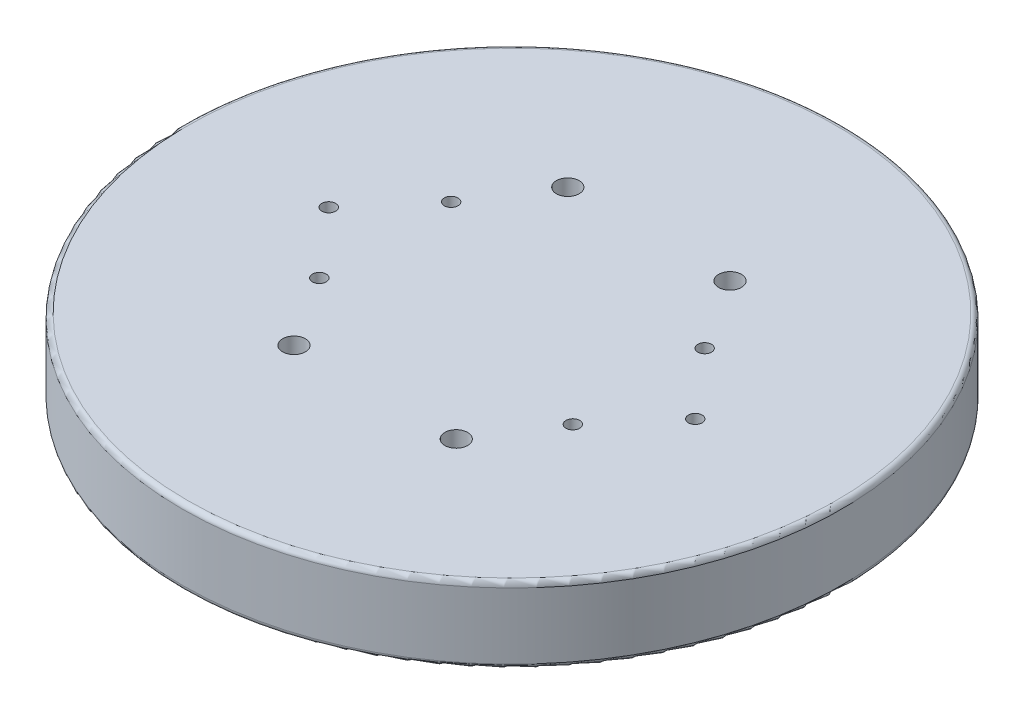
SolidWorks part; units mm, degrees
material "Delrin 2700 NC010, Low Viscosity Acetal Copolymer (SS)"
ref_plane "Front Plane" through (0, 0, 0) normal (0, 0, 1) x (1, 0, 0)
ref_plane "Top Plane" through (0, 0, 0) normal (0, 1, 0) x (1, 0, 0)
ref_plane "Right Plane" through (0, 0, 0) normal (1, 0, 0) x (0, 0, -1)
sketch "Sketch1" plane through (0, 0, 0) normal (0, 1, 0) x (1, 0, 0)
  circle A0 centre (0, 0) radius 65
  dimension "D1" = 130
extrude "Boss-Extrude1" add sketch "Sketch1" along normal blind 15
fillet "Fillet1" radius 1 2 edges at (0, 0, 65) (0, 15, 65)
hole_wizard "#6-32 Tapped Hole1" positions "Sketch2" profile "Sketch3" tap size "#6-32" standard "ANSI Inch" end condition through all
sketch "Sketch2" plane through (0, 0, 0) normal (0, 1, 0) x (1, 0, 0)
  point P0 (-36.145, 0)
  point P2 (36.145, 0)
  point P4 (-25, 13)
  point P6 (-25, -13)
  point P8 (25, -13)
  point P10 (25, 13)
  dimension "D1" = 36.145
  dimension "D2" = 36.145
  dimension "D3" = 25
  dimension "D4" = 25
  dimension "D5" = 13
  dimension "D6" = 13
sketch "Sketch3" plane through (-36.145, 0, 0) normal (1, 0, 0) x (0, 0, -1)
  line L0 (0, 0) -> (0, 15)
  line L1 (0, 15) -> (1.3525, 15)
  line L2 (1.3525, 15) -> (1.3525, 0)
  line L5 (1.3525, 0) -> (0, 0)
  line L11 (0, -6.35) -> (0, 107.95) construction
  dimension "Thru Tap Drill Dia." = 2.7051
  dimension "Thru Tap Drill Depth" = 15
cosmetic thread "Hole Thread1" parameters "D2"=3.5052
cosmetic thread "Hole Thread2" parameters "D2"=3.5052
cosmetic thread "Hole Thread3" parameters "D2"=3.5052
cosmetic thread "Hole Thread4" parameters "D2"=3.5052
cosmetic thread "Hole Thread5" parameters "D2"=3.5052
cosmetic thread "Hole Thread6" parameters "D2"=3.5052
hole_wizard "#4-40 Tapped Hole1" [suppressed] positions "Sketch5" profile "Sketch6" tap size "#4-40" standard "ANSI Inch"
sketch "Sketch5" plane through (0, 0, 0) normal (0, -1, 0) x (-1, 0, 0)
  circle A0 centre (-36.145, 0) radius 1.3526 construction
  point P0 (-48.145, 27.124)
  point P2 (-48.145, -27.124)
  dimension "D1" = 12
  dimension "D2" = 27.124
  dimension "D3" = 27.124
sketch "Sketch6" plane through (48.145, 0, -27.124) normal (1, 0, 0) x (0, 0, -1)
  line L0 (0, 0) -> (0, 25.4)
  line L1 (0, 25.4) -> (1.1303, 25.4)
  line L2 (1.1303, 25.4) -> (1.1303, 0)
  line L5 (1.1303, 0) -> (0, 0)
  line L11 (0, -6.35) -> (0, 107.95) construction
  dimension "Thru Tap Drill Dia." = 2.2606
  dimension "Thru Tap Drill Depth" = 25.4
cosmetic thread "Hole Thread7" [suppressed] parameters "D2"=2.8448
cosmetic thread "Hole Thread8" [suppressed] parameters "D2"=2.8448
hole_wizard "#8 Clearance Hole1" positions "Sketch7" profile "Sketch8" hole size "#8" standard "ANSI Inch" end condition through all
sketch "Sketch7" plane through (0, 0, 0) normal (0, -1, 0) x (-1, 0, 0)
  point P0 (16, -27)
  point P2 (-16, -27)
  point P4 (16, 27)
  point P6 (-16, 27)
  dimension "D1" = 16
  dimension "D2" = 16
  dimension "D3" = 27
  dimension "D4" = 27
sketch "Sketch8" plane through (-16, 0, 27) normal (1, 0, 0) x (0, 0, -1)
  line L0 (0, 0) -> (0, 15)
  line L1 (0, 15) -> (2.2479, 15)
  line L2 (2.2479, 15) -> (2.2479, 0)
  line L5 (2.2479, 0) -> (0, 0)
  line L11 (0, -6.35) -> (0, 107.95) construction
  dimension "Thru Hole Dia." = 4.4958
  dimension "Thru Hole Depth" = 15
equation "\"D2@Sketch2\"=\"D1@Sketch2\""
equation "\"D4@Sketch2\"=\"D3@Sketch2\""
equation "\"D6@Sketch2\"=\"D5@Sketch2\""
equation "\"D2@Sketch5\"=\"D3@Sketch5\""
equation "\"D2@Sketch7\"=\"D1@Sketch7\""
equation "\"D3@Sketch7\"=\"D4@Sketch7\""
